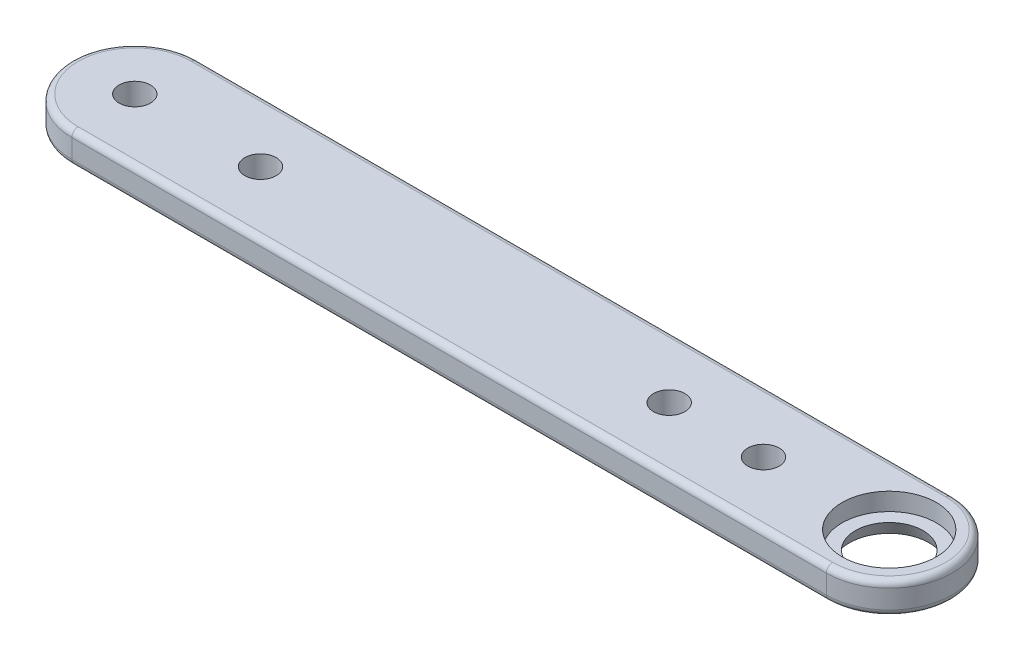
SolidWorks part; units mm, degrees
material "Plain Carbon Steel"
ref_plane "Front Plane" through (0, 0, 0) normal (0, 0, 1) x (1, 0, 0)
ref_plane "Top Plane" through (0, 0, 0) normal (0, 1, 0) x (1, 0, 0)
ref_plane "Right Plane" through (0, 0, 0) normal (1, 0, 0) x (0, 0, -1)
sketch "Sketch1" plane through (0, 0, 0) normal (0, 1, 0) x (1, 0, 0)
  line L1 (88.9, -12.7) -> (-88.9, -12.7)
  line L2 (88.9, -12.7) -> (88.9, 12.7)
  line L3 (88.9, 12.7) -> (-88.9, 12.7)
  line L4 (-88.9, -12.7) -> (-88.9, 12.7)
  line L5 (88.9, -12.7) -> (-88.9, 12.7) construction
  line L6 (88.9, 12.7) -> (-88.9, -12.7) construction
  point P0 (0, 0)
  dimension "D1" = 25.4
  dimension "D2" = 177.8
extrude "Boss-Extrude1" add sketch "Sketch1" along normal blind 6.35
sketch "Sketch2" plane through (0, 6.35, 0) normal (0, 1, 0) x (1, 0, 0)
  line L0 (-88.9, 0) -> (88.9, 0) construction
  line L1 (-88.9, 12.7) -> (-88.9, -12.7) construction
  line L2 (88.9, -12.7) -> (88.9, 12.7) construction
  circle A0 centre (-76.2, 0) radius 3.175
  circle A3 centre (76.2, 0) radius 6.35
  circle A7 centre (-50.8, 0) radius 3.175
  dimension "D1" = 12.7
  dimension "D4" = 6.35
  dimension "D2" = 152.4
  dimension "D3" = 12.7
  dimension "D5" = 2
extrude "Cut-Extrude1" cut sketch "Sketch2" against normal through all
sketch "Sketch3" plane through (0, 6.35, 0) normal (0, 1, 0) x (1, 0, 0)
  circle A0 centre (76.2, 0) radius 9.525
  dimension "D1" = 19.05
extrude "Cut-Extrude2" cut sketch "Sketch3" against normal blind 3.5719
sketch "Sketch4" plane through (0, 6.35, 0) normal (0, 1, 0) x (1, 0, 0)
  line L0 (-88.9, 0) -> (88.9, 0) construction
  circle A0 centre (50.8, 0) radius 3.175
  circle A2 centre (31.75, 0) radius 3.175
  dimension "D3" = 6.35
  dimension "D1" = 25.4
  dimension "D2" = 19.05
extrude "Cut-Extrude3" cut sketch "Sketch4" against normal through all
sketch "Sketch5" plane through (0, 6.35, 0) normal (0, 1, 0) x (1, 0, 0)
  line L0 (88.9, -12.7) -> (88.9, 12.7) construction
  line L3 (-88.9, 12.7) -> (-88.9, -12.7) construction
  circle A2 centre (-76.2, 0) radius 12.7
  circle A3 centre (76.2, 0) radius 12.7
  line M11 (88.9, -12.7) -> (88.9, 12.7)
  line M13 (-88.9, 12.7) -> (-88.9, -12.7)
  line M25 (-88.9, -12.7) -> (88.9, -12.7)
  line M26 (88.9, 12.7) -> (-88.9, 12.7)
extrude "Cut-Extrude4" cut sketch "Sketch5" against normal through all contours A3 M11 M26 | A3 M25 M11 | A2 M26 M13 | A2 M13 M25
fillet "Fillet1" radius 1.27 8 edges at (0, 0, -12.7) (0, 6.35, -12.7) (0, 0, 12.7) (0, 6.35, 12.7) (-88.9, 0, 0) (-88.9, 6.35, 0) (88.9, 0, 0) (88.9, 6.35, 0)
ref_axis "Axis1" through (76.2, 0, 0) along (0, 1, 0)
ref_plane "Plane1" through (76.2, 0, 0) normal (-1, 0, 0) x (0, 0, 1)
sketch "Sketch6" plane through (76.2, 0, 0) normal (-1, 0, 0) x (0, 0, 1)
  line L0 (0, 0) -> (0, 6.35)
  line L1 (11.43, 6.35) -> (-11.43, 6.35) construction
  line L2 (0, 6.35) -> (-3.6942, -1.9474)
  line L3 (-3.6942, -1.9474) -> (-8.0682, 0)
  line L4 (-8.0682, 0) -> (-4.374, 8.2974)
  line L5 (-4.374, 8.2974) -> (0, 6.35)
  line L6 (-11.43, 0) -> (11.43, 0) construction
  line L7 (0, 0) -> (-6.35, 0)
  line L8 (-6.35, 0) -> (-6.35, 2.7781)
  line L9 (-6.35, 2.7781) -> (0, 2.7781)
  line L10 (-6.35, 0) -> (-8.0682, 0)
  line L11 (-6.35, 2.7781) -> (-6.8313, 2.7781)
  dimension "D1" = 24
  dimension "D2" = 4.7879
  dimension "D3" = 6.35
  dimension "D4" = 2.7781
revolve "Cut-Revolve2" cut sketch "Sketch6" angle 360 about axis through (76.2, 0, 0) along (0, 1, 0)
